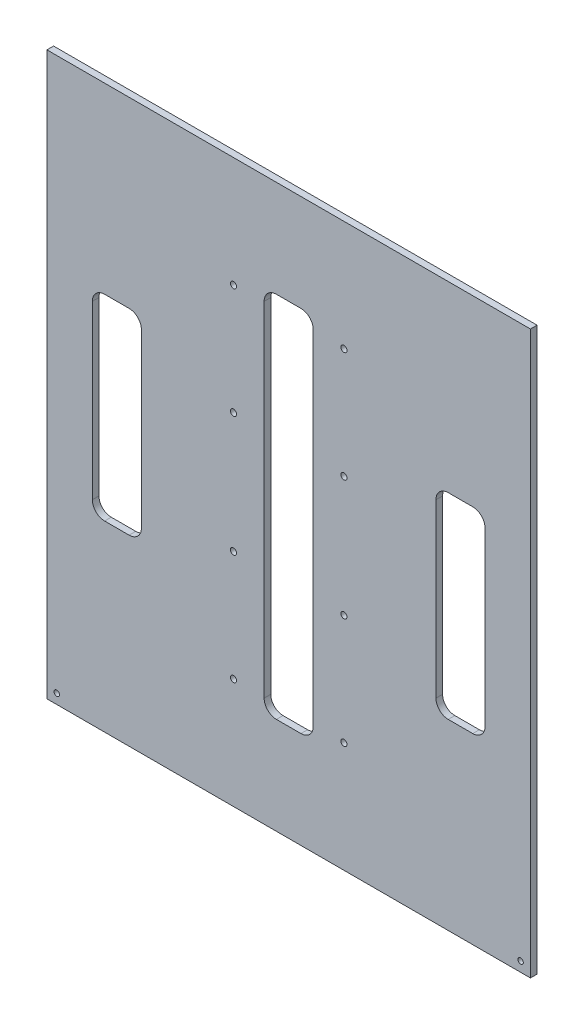
SolidWorks part; units mm, degrees
ref_plane "前视基准面" through (0, 0, 0) normal (0, 0, 1) x (1, 0, 0)
ref_plane "上视基准面" through (0, 0, 0) normal (0, 1, 0) x (1, 0, 0)
ref_plane "右视基准面" through (0, 0, 0) normal (1, 0, 0) x (0, 0, -1)
other "Configuration Table"
sketch "草图1" plane through (0, 0, 0) normal (0, 0, 1) x (1, 0, 0)
  line L1 (0, 0) -> (197, 0)
  line L2 (0, 0) -> (0, 229)
  line L3 (0, 229) -> (197, 229)
  line L4 (197, 0) -> (197, 229)
  line L5 (0, 0) -> (197, 229) construction
  line L6 (0, 229) -> (197, 0) construction
  point P4 (98.5, 114.5)
  dimension "D1" = 197
  dimension "D2" = 229
extrude "凸台-拉伸1" add sketch "草图1" along normal blind 2.7
sketch "草图2" plane through (0, 0, 2.7) normal (0, 0, 1) x (1, 0, 0)
  line L0 (0, 0) -> (197, 0) construction
  line L1 (0, 229) -> (0, 0) construction
  line L2 (197, 0) -> (197, 229) construction
  circle A0 centre (4, 4) radius 1.1
  circle A1 centre (4, 4) radius 2.5 construction
  circle A2 centre (193, 4) radius 1.1
  dimension "D1" = 2.2
  dimension "D4" = 5
  dimension "D5" = 2.2
  dimension "D2" = 4
  dimension "D3" = 4
  dimension "D6" = 4
  dimension "D7" = 4
extrude "切除-拉伸1" cut sketch "草图2" against normal blind 2.85
sketch "草图3" plane through (0, 0, 0) normal (0, 0, -1) x (-1, 0, 0)
  line L0 (-98.5, 229) -> (-98.5, 0) construction
  line L1 (-197, 114.5) -> (0, 114.5) construction
  line L2 (-133.1, 12.9) -> (-63.9, 12.9) construction
  line L3 (-136, 85) -> (-61, 85) construction
  line L4 (0, 0) -> (0, 229)
  line L5 (0, 229) -> (-197, 229)
  line L6 (-197, 229) -> (-197, 0)
  line L7 (-197, 0) -> (0, 0)
  line L8 (0, 0) -> (0, 229) construction
  line L9 (0, 229) -> (-197, 229) construction
  line L10 (-197, 229) -> (-197, 0) construction
  line L11 (-197, 0) -> (0, 0) construction
  line L12 (-136, 85) -> (-136, 10) construction
  line L13 (-136, 10) -> (-61, 10) construction
  line L14 (-61, 85) -> (-61, 10) construction
  line L15 (-136, 85) -> (-61, 10) construction
  line L16 (-136, 10) -> (-61, 85) construction
  circle A0 centre (-133.1, 12.9) radius 1.35
  circle A1 centre (-133.1, 82.1) radius 1.35
  circle A2 centre (-63.9, 82.1) radius 1.35
  circle A3 centre (-63.9, 12.9) radius 1.35
  point P12 (-98.5, 47.5)
  point P21 (-98.5, 12.9)
  dimension "D4" = 2.7
  dimension "D5" = 2.7
  dimension "D6" = 2.7
  dimension "D7" = 2.7
  dimension "D2" = 75
  dimension "D3" = 75
  dimension "D8" = 69.2
  dimension "D9" = 69.2
  dimension "D10" = 69.2
  dimension "D11" = 69.2
  dimension "D12" = 2.9
  dimension "D13" = 2.9
  dimension "D14" = 10
  dimension "D1" = 0
extrude "切除-拉伸2" [suppressed] cut sketch "草图3" against normal blind 9
sketch "草图4" [suppressed] plane through (0, 0, 0) normal (0, 0, -1) x (-1, 0, 0)
  line L0 (-133.1, 27.9) -> (-133.1, 220.1492) construction
  line L1 (-63.9, 12.9) -> (-63.9, 193.6705) construction
sketch "草图5" plane through (0, 0, 0) normal (0, 0, -1) x (-1, 0, 0)
  line L0 (-98.5, 229) -> (-98.5, 0) construction
  line L1 (-197, 229) -> (0, 229) construction
  circle A0 centre (-132.5, 214) radius 1.75
  circle A1 centre (-64.5014, 213.5596) radius 1.75
  circle A2 centre (-132.5, 123.4) radius 1.75
  circle A3 centre (-64.5, 122.9596) radius 1.75
  dimension "D5" = 3.5
  dimension "D6" = 3.5
  dimension "D7" = 3.5
  dimension "D8" = 3.5
  dimension "D1" = 68
  dimension "D2" = 34
  dimension "D3" = 34
  dimension "D4" = 34
  dimension "D9" = 90.6
  dimension "D10" = 90.6
  dimension "D11" = 15
  dimension "D12" = 33.9986
extrude "切除-拉伸3" [suppressed] cut sketch "草图5" against normal blind 10
sketch "草图6" plane through (0, 0, 0) normal (0, 0, -1) x (-1, 0, 0)
  line L0 (-98.5, 229) -> (-98.5, 0) construction
  line L1 (-178.5, 154.5) -> (-158.5, 154.5)
  line L2 (-178.5, 154.5) -> (-178.5, 74.5)
  line L3 (-178.5, 74.5) -> (-158.5, 74.5)
  line L4 (-158.5, 154.5) -> (-158.5, 74.5)
  line L5 (-178.5, 154.5) -> (-158.5, 74.5) construction
  line L6 (-178.5, 74.5) -> (-158.5, 154.5) construction
  line L7 (-38.5, 154.5) -> (-18.5, 154.5)
  line L8 (-38.5, 154.5) -> (-38.5, 74.5)
  line L9 (-38.5, 74.5) -> (-18.5, 74.5)
  line L10 (-18.5, 154.5) -> (-18.5, 74.5)
  line L11 (-38.5, 154.5) -> (-18.5, 74.5) construction
  line L12 (-38.5, 74.5) -> (-18.5, 154.5) construction
  line L13 (-108.5, 189.5) -> (-88.5, 189.5)
  line L14 (-108.5, 189.5) -> (-108.5, 39.5)
  line L15 (-108.5, 39.5) -> (-88.5, 39.5)
  line L16 (-88.5, 189.5) -> (-88.5, 39.5)
  line L17 (-108.5, 189.5) -> (-88.5, 39.5) construction
  line L18 (-108.5, 39.5) -> (-88.5, 189.5) construction
  line L19 (-197, 229) -> (0, 229) construction
  line L20 (0, 0) -> (-197, 0) construction
  line L21 (-197, 114.5) -> (0, 114.5) construction
  line L22 (-197, 0) -> (-197, 229) construction
  line L23 (0, 229) -> (0, 0) construction
  point P4 (-168.5, 114.5)
  point P9 (-28.5, 114.5)
  point P14 (-98.5, 114.5)
  dimension "D1" = 70
  dimension "D2" = 70
  dimension "D3" = 20
  dimension "D4" = 20
  dimension "D5" = 80
  dimension "D6" = 80
  dimension "D7" = 150
  dimension "D8" = 20
extrude "切除-拉伸4" cut sketch "草图6" against normal blind 10
fillet "圆角1" radius 5 12 edges at (88.5, 39.5, 1.35) (108.5, 39.5, 1.35) (108.5, 189.5, 1.35) (18.5, 154.5, 1.35) (18.5, 74.5, 1.35) (38.5, 74.5, 1.35) (38.5, 154.5, 1.35) (158.5, 154.5, 1.35) (158.5, 74.5, 1.35) (178.5, 74.5, 1.35) (178.5, 154.5, 1.35) (88.5, 189.5, 1.35)
sketch "草图7" plane through (0, 0, 2.7) normal (0, 0, 1) x (1, 0, 0)
  line L0 (98.5, 229) -> (98.5, 0) construction
  line L1 (76, 184) -> (121, 184) construction
  line L2 (121, 184) -> (121, 139) construction
  line L3 (76, 139) -> (121, 139) construction
  line L4 (197, 229) -> (0, 229) construction
  line L5 (0, 114.5) -> (197, 114.5) construction
  line L6 (0, 229) -> (0, 0) construction
  line L7 (197, 0) -> (197, 229) construction
  line L8 (76, 90) -> (121, 90) construction
  line L9 (121, 45) -> (121, 90) construction
  line L10 (76, 45) -> (121, 45) construction
  circle A0 centre (76, 184) radius 1.25
  circle A1 centre (121, 184) radius 1.25
  circle A2 centre (76, 139) radius 1.25
  circle A3 centre (121, 139) radius 1.25
  circle A4 centre (121, 90) radius 1.25
  circle A5 centre (76, 90) radius 1.25
  circle A6 centre (121, 45) radius 1.25
  circle A7 centre (76, 45) radius 1.25
  point P10 (98.5, 184)
  point P11 (98.5, 139)
  dimension "D1" = 2.5
  dimension "D2" = 45
  dimension "D3" = 45
  dimension "D4" = 45
extrude "切除-拉伸5" cut sketch "草图7" against normal blind 10
